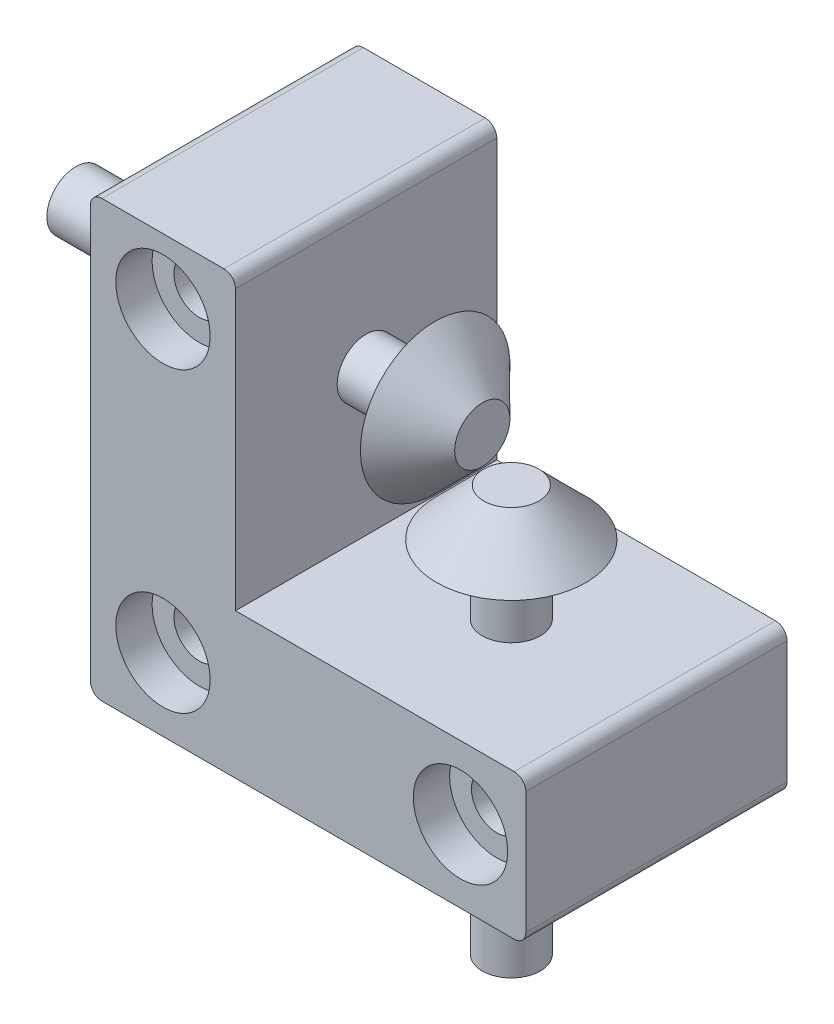
SolidWorks part; units mm, degrees
material "Chromium Copper, UNS C18200"
ref_plane "Front Plane" through (0, 0, 0) normal (0, 0, 1) x (1, 0, 0)
ref_plane "Top Plane" through (0, 0, 0) normal (0, 1, 0) x (1, 0, 0)
ref_plane "Right Plane" through (0, 0, 0) normal (1, 0, 0) x (0, 0, -1)
sketch "Sketch1" plane through (0, 0, 0) normal (0, 0, 1) x (1, 0, 0)
  line L0 (0, 0) -> (0, 30)
  line L1 (0, -55) -> (0, 55) construction
  line L2 (0, 30) -> (10, 30)
  line L3 (10, 30) -> (10, 10)
  line L4 (10, 10) -> (30, 10)
  line L5 (30, 10) -> (30, 0)
  line L6 (55, 0) -> (-55, 0) construction
  line L7 (30, 0) -> (0, 0)
  dimension "D1" = 30
  dimension "D2" = 10
  dimension "D3" = 10
  dimension "D4" = 30
extrude "Boss-Extrude2" add sketch "Sketch1" along normal blind 18 contours L4 L5 L7 L0 L2 L3
sketch "Sketch2" plane through (0, 0, 0) normal (0, 0, -1) x (-1, 0, 0)
  line L0 (-30, 5) -> (5.0203, 5) construction
  line L1 (-30, 10) -> (-30, 0) construction
  line L2 (-5, 30) -> (-5, -3.3076) construction
  line L3 (0, 30) -> (-10, 30) construction
  circle A0 centre (-25.5, 5) radius 1.75
  circle A1 centre (-5, 5) radius 1.75
  circle A2 centre (-5, 25.5) radius 1.75
  dimension "D3" = 3.5
  dimension "D4" = 3.5
  dimension "D5" = 3.5
  dimension "D1" = 4.5
  dimension "D2" = 4.5
extrude "Cut-Extrude1" cut sketch "Sketch2" against normal up to surface (18 mm away) up to face at (13.3333, 13.3333, 18)
sketch "Sketch3" plane through (0, 0, 0) normal (0, 0, -1) x (-1, 0, 0)
  circle A0 centre (-25.5, 5) radius 3.25
  circle A1 centre (-5, 5) radius 3.25
  circle A2 centre (-5, 25.5) radius 3.25
  dimension "D1" = 6.5
  dimension "D2" = 6.5
  dimension "D3" = 6.5
extrude "Cut-Extrude2" cut sketch "Sketch3" against normal blind 2.5
ref_plane "Plane1" through (0, 0, 9) normal (0, 0, 1) x (1, 0, 0)
mirror "Mirror1" about plane through (0, 0, 9) normal (0, 0, 1) of "Cut-Extrude2"
fillet "Fillet1" radius 0.8 5 edges at (0, 0, 9) (30, 0, 9) (0, 30, 9) (10, 30, 9) (30, 10, 9)
sketch "Sketch4" plane through (0, 0, 0) normal (0, -1, 0) x (1, 0, 0)
  line L0 (16.5, 9) -> (-16.5, 9) construction
  line L1 (30, 18) -> (30, 0) construction
  circle A0 centre (20, 9) radius 2
  dimension "D2" = 4
  dimension "D1" = 10
extrude "Boss-Extrude3" add sketch "Sketch4" along normal blind 10
ref_plane "Plane2" through (0, 0, 0) normal (0.7071, -0.7071, 0) x (0, 0, -1)
mirror "Mirror2" about plane through (0, 0, 0) normal (0.7071, -0.7071, 0) of "Boss-Extrude3"
sketch "Sketch5" plane through (0, 0, 9) normal (0, 0, 1) x (1, 0, 0)
  line L0 (0, 0) -> (29.5057, 29.5057) construction
  line L1 (-7.0004, -7.0004) -> (7.0004, 7.0004) construction
  line L2 (18, 10) -> (18, 14.7529)
  line L3 (10, 10) -> (29.2, 10) construction
  line L11 (20, 23.8733) -> (20, -14.4081) construction
  line L13 (20, 18) -> (20, 10)
  line L14 (20, 10) -> (18, 10)
  line L15 (18, 14.7529) -> (14.85, 14.7529)
  line L16 (14.85, 14.7529) -> (18.0971, 18)
  line L17 (18.0971, 18) -> (20, 18)
  dimension "D1" = 3.15
revolve "Revolve4" add sketch "Sketch5" angle 360 about L11
mirror "Mirror7" about plane through (0, 0, 0) normal (0.7071, -0.7071, 0) of "Revolve4"
